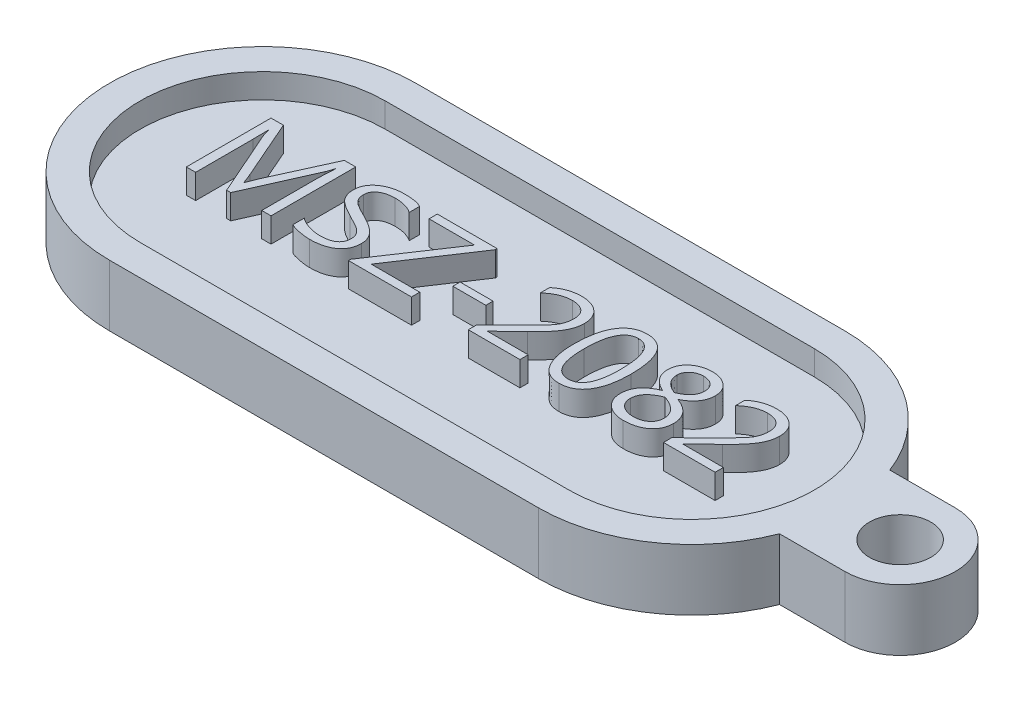
SolidWorks part; units mm, degrees
ref_plane "前基準面" through (0, 0, 0) normal (0, 0, 1) x (1, 0, 0)
ref_plane "上基準面" through (0, 0, 0) normal (0, 1, 0) x (1, 0, 0)
ref_plane "右基準面" through (0, 0, 0) normal (1, 0, 0) x (0, 0, -1)
sketch "草圖1" plane through (0, 0, 0) normal (0, 1, 0) x (1, 0, 0)
  line L0 (0, 0) -> (35, 0) construction
  line L1 (0, 12.5) -> (35, 12.5)
  line L2 (0, -12.5) -> (35, -12.5)
  line L3 (47.5, 0) -> (47.5, 23.3491) construction
  line L4 (-12.5, 0) -> (-12.5, 27.7516) construction
  arc A0 (0, 12.5) -> (0, -12.5) centre (0, 0) ccw
  arc A1 (35, -12.5) -> (35, 12.5) centre (35, 0) ccw
  point P3 (17.5, 0)
  dimension "D1" = 12.5
  dimension "D2" = 60
extrude "填料-伸長1" add sketch "草圖1" along normal blind 5
sketch "草圖2" plane through (0, 5, 0) normal (0, 1, 0) x (1, 0, 0)
  line L4 (0, -10) -> (35, -10)
  line L5 (35, 10) -> (0, 10)
  line L6 (0, -10) -> (35, -10)
  line L7 (35, 10) -> (0, 10)
  arc A4 (0, 10) -> (0, -10) centre (0, 0) ccw
  arc A5 (35, -10) -> (35, 10) centre (35, 0) ccw
  arc A6 (0, 10) -> (0, -10) centre (0, 0) ccw
  arc A7 (35, -10) -> (35, 10) centre (35, 0) ccw
  dimension "D1" = 2.5
extrude "除料-伸長1" cut sketch "草圖2" against normal blind 2
sketch "草圖3" plane through (0, 3, 0) normal (0, 1, 0) x (1, 0, 0)
  text T0 "MSZ-2082" font "微軟正黑體" height in points 22
extrude "填料-伸長2" add sketch "草圖3" along normal blind 2
sketch "草圖4" plane through (0, 5, 0) normal (0, 1, 0) x (1, 0, 0)
  line L0 (47.5, 0) -> (52, 0) construction
  line L1 (52, 4.5) -> (46.6619, 4.5)
  line L2 (52, -4.5) -> (46.6619, -4.5)
  arc A0 (35, -12.5) -> (35, 12.5) centre (35, 0) ccw construction
  arc A1 (46.6619, -4.5) -> (46.6619, 4.5) centre (35, 0) ccw
  arc A2 (52, 4.5) -> (52, -4.5) centre (52, 0) cw
  point P10 (0, 0)
  point P11 (0, 0)
  dimension "D1" = 4.5
  dimension "D2" = 4.5
extrude "填料-伸長3" add sketch "草圖4" against normal blind 5
sketch "草圖5" plane through (0, 5, 0) normal (0, 1, 0) x (1, 0, 0)
  circle A0 centre (52, 0) radius 2.5
  dimension "D1" = 5
extrude "除料-伸長2" cut sketch "草圖5" against normal through all
